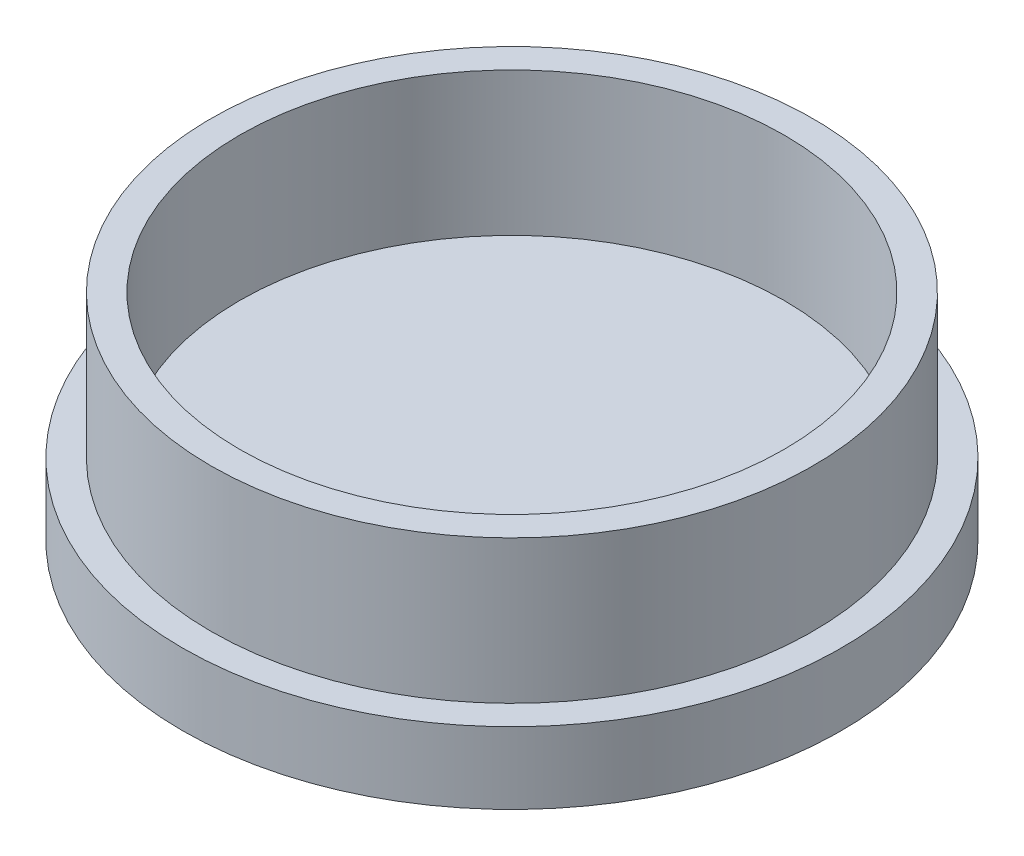
SolidWorks part; units mm, degrees
material "PLA плотность"
ref_plane "Спереди" through (0, 0, 0) normal (0, 0, 1) x (1, 0, 0)
ref_plane "Сверху" through (0, 0, 0) normal (0, 1, 0) x (1, 0, 0)
ref_plane "Справа" through (0, 0, 0) normal (1, 0, 0) x (0, 0, -1)
sketch "Эскиз1" plane through (0, 0, 0) normal (0, 1, 0) x (1, 0, 0)
  circle A0 centre (0, 0) radius 23
extrude "Бобышка-Вытянуть1" add sketch "Эскиз1" along normal blind 5
sketch "Эскиз3" plane through (0, 5, 0) normal (0, 1, 0) x (1, 0, 0)
  circle A0 centre (0, 0) radius 21
  circle A1 centre (0, 0) radius 19
extrude "Бобышка-Вытянуть2" add sketch "Эскиз3" along normal blind 10
